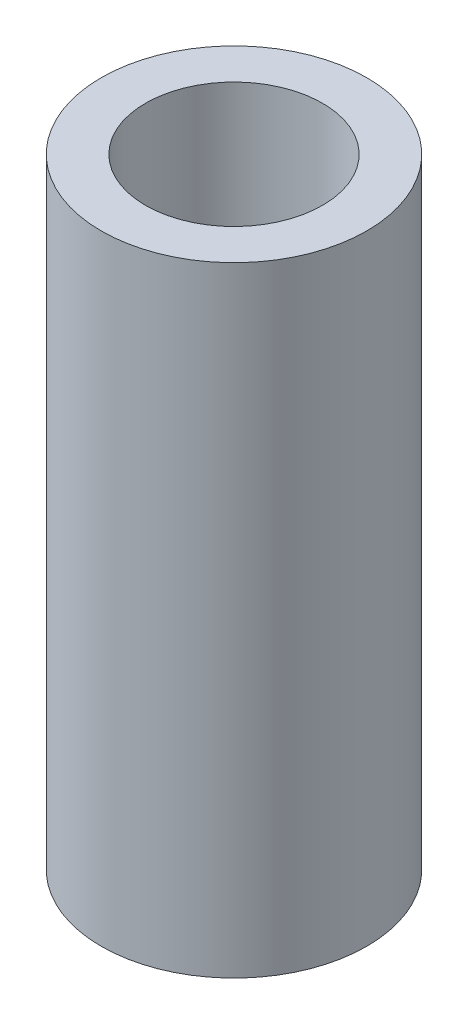
SolidWorks part; units mm, degrees
material "Brass"
ref_plane "Front Plane" through (0, 0, 0) normal (0, 0, 1) x (1, 0, 0)
ref_plane "Top Plane" through (0, 0, 0) normal (0, 1, 0) x (1, 0, 0)
ref_plane "Right Plane" through (0, 0, 0) normal (1, 0, 0) x (0, 0, -1)
sketch "Sketch1" plane through (0, 0, 0) normal (0, 0, 1) x (1, 0, 0)
  line L0 (-3, 0) -> (0, 0)
  line L1 (0, 0) -> (0, 14)
  line L3 (0, 14) -> (-3, 14)
  line L5 (-3, 14) -> (-3, 0)
  line L6 (0, -2.69) -> (0, 16.8158) construction
  point P2 (0, 0)
  point P7 (0, 0)
  point P10 (0, 0)
  point P11 (0, 0)
  point P12 (-1.0551, 14)
  point P13 (0, 0)
  point P14 (0, 0)
  point P15 (0, 0)
  point P16 (0, 0)
  dimension "D1" = 14
  dimension "D2" = 3
revolve "Revolve1" add sketch "Sketch1" angle 360 about L6
sketch "Sketch2" plane through (0, 0, 0) normal (0, 1, 0) x (1, 0, 0)
  circle A0 centre (0, 0) radius 2
  dimension "D1" = 4
extrude "Cut-Extrude1" cut sketch "Sketch2" along normal through all
